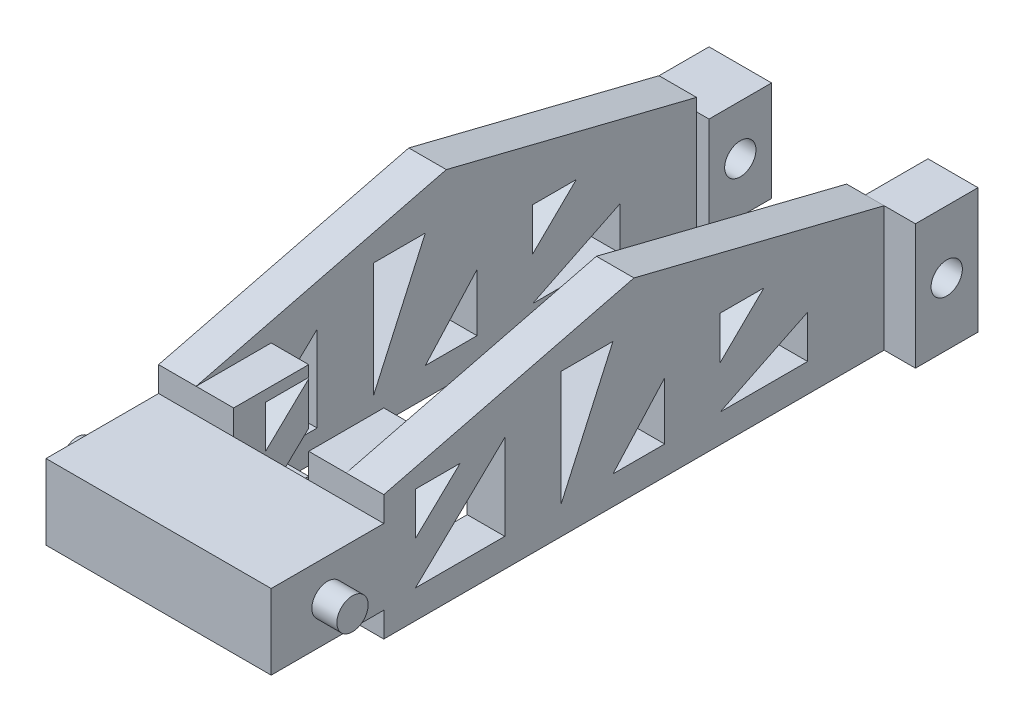
SolidWorks part; units mm, degrees
ref_plane "Front Plane" through (0, 0, 0) normal (0, 0, 1) x (1, 0, 0)
ref_plane "Top Plane" through (0, 0, 0) normal (0, 1, 0) x (1, 0, 0)
ref_plane "Right Plane" through (0, 0, 0) normal (1, 0, 0) x (0, 0, -1)
sketch "Sketch1" plane through (0, 0, 0) normal (1, 0, 0) x (0, 0, -1)
  circle A0 centre (0, 0) radius 12.5
  dimension "D1" = 25
extrude "Boss-Extrude1" add sketch "Sketch1" along normal blind 20
sketch "Sketch2" plane through (20, 0, 0) normal (1, 0, 0) x (0, 0, -1)
  line L0 (45, 30) -> (45, -30)
  line L2 (-45, 30) -> (-45, -30)
  line L3 (-45, -30) -> (45, -30)
  line L8 (-45, 30) -> (45, 30)
  line L13 (45, -30) -> (-45, 30) construction
  line L14 (45, 30) -> (-45, -30) construction
  point P0 (0, 0)
  point P2 (0, 0)
  point P8 (75, 0)
extrude "Boss-Extrude2" add sketch "Sketch2" along normal blind 90
mirror "Mirror1" about plane through (110, 0, 0) normal (-1, 0, 0) of bodies 102
sketch "Sketch6" plane through (0, 0, -45) normal (0, 0, -1) x (-1, 0, 0)
  line L1 (-140, 0) -> (-110, 0) construction
  line L3 (-20, -50) -> (-80, -50)
  line L4 (-80, 50) -> (-80, -50)
  line L5 (-20, 50) -> (-80, 50)
  line L7 (-20, 50) -> (-20, -50)
  line L8 (-200, 50) -> (-140, 50)
  line L9 (-200, 50) -> (-200, -50)
  line L10 (-200, -50) -> (-140, -50)
  line L11 (-140, 50) -> (-140, -50)
  dimension "D1" = 60
  dimension "D2" = 100
extrude "Boss-Extrude4" add sketch "Sketch6" along normal blind 400
sketch "Sketch8" plane through (0, 50, 0) normal (0, 1, 0) x (1, 0, 0)
  line L0 (20, 445) -> (80, 445) construction
  line L9 (50, 445) -> (170, 445)
  line L10 (50, 445) -> (50, 105)
  line L11 (50, 105) -> (170, 105)
  line L12 (170, 445) -> (170, 105)
extrude "Cut-Extrude4" cut sketch "Sketch8" against normal through all
sketch "Sketch9" plane through (20, 0, 0) normal (-1, 0, 0) x (0, 0, 1)
  line L2 (-445, 50) -> (-245, 100)
  line L5 (-45, 50) -> (-245, 100)
  line L8 (-445, 50) -> (-45, 50)
extrude "Boss-Extrude5" add sketch "Sketch9" against normal up to surface (30 mm away) up to face at (50, 0, -275)
sketch "Sketch10" plane through (200, 0, 0) normal (1, 0, 0) x (0, 0, -1)
  line L2 (245, 100) -> (445, 50)
  line L6 (245, 100) -> (45, 50)
  line L9 (45, 50) -> (445, 50)
extrude "Boss-Extrude6" add sketch "Sketch10" against normal up to vertex
sketch "Sketch11" plane through (200, 0, 0) normal (1, 0, 0) x (0, 0, -1)
  line L0 (70.2948, 6.9541) -> (106.0107, 41.1662)
  line L1 (70.2948, 41.1662) -> (106.0107, 41.1662)
  line L2 (70.2948, 41.1662) -> (70.2948, 6.9541)
  line L3 (70.2948, -27.258) -> (141.7267, -27.258)
  line L4 (141.7267, 41.1662) -> (141.7267, -27.258)
  line L5 (186.8415, 64.4755) -> (228.1968, 64.4755)
  line L6 (186.8415, 64.4755) -> (186.8415, -27.258)
  line L9 (228.1968, -27.258) -> (269.5521, -27.258)
  line L10 (269.5521, 18.6087) -> (269.5521, -27.258)
  line L11 (313.915, 41.1662) -> (348.879, 41.1662)
  line L12 (313.915, 41.1662) -> (313.915, 6.9541)
  line L13 (313.915, -27.258) -> (383.843, -27.258)
  line L14 (383.843, 6.9541) -> (383.843, -27.258)
  line L15 (70.2948, -27.258) -> (141.7267, 41.1662)
  line L16 (186.8415, -27.258) -> (228.1968, 64.4755)
  line L17 (228.1968, -27.258) -> (269.5521, 18.6087)
  line L18 (313.915, 6.9541) -> (348.879, 41.1662)
  line L19 (313.915, -27.258) -> (383.843, 6.9541)
  point P12 (245, 0)
extrude "Cut-Extrude6" cut sketch "Sketch11" against normal up to vertex (180 mm away) up to point (20, -50, -445)
sketch "Sketch12" plane through (0, 0, -445) normal (0, 0, -1) x (-1, 0, 0)
  line L0 (-35, 50) -> (-35, -50) construction
  line L1 (-20, 50) -> (-50, 50) construction
  line L2 (-50, -50) -> (-20, -50) construction
  line L4 (-60, -40) -> (-10, -40)
  line L5 (-60, -40) -> (-60, 40)
  line L6 (-60, 40) -> (-10, 40)
  line L7 (-10, -40) -> (-10, 40)
  line L8 (-60, -40) -> (-10, 40) construction
  line L9 (-60, 40) -> (-10, -40) construction
  point P6 (-35, 0)
  point P7 (-35, 0)
  dimension "D1" = 50
  dimension "D2" = 80
extrude "Boss-Extrude7" add sketch "Sketch12" along normal blind 50
sketch "Sketch14" plane through (0, 0, -445) normal (0, 0, -1) x (-1, 0, 0)
  line L0 (-185, 50) -> (-185, -50)
  line L1 (-170, 50) -> (-200, 50) construction
  line L2 (-200, -50) -> (-170, -50) construction
  line L3 (-185, -50) -> (-225, -50)
  line L4 (-225, -50) -> (-225, 50)
  line L5 (-225, 50) -> (-185, 50)
  dimension "D1" = 40
extrude "Boss-Extrude8" add sketch "Sketch14" along normal through all
sketch "Sketch13" plane through (60, 0, 0) normal (1, 0, 0) x (0, 0, -1)
  line L0 (470, 0) -> (445, 0) construction
  line L3 (445, 40) -> (445, -40) construction
  circle A0 centre (470, 0) radius 12.5
  dimension "D1" = 25
extrude "Cut-Extrude7" cut sketch "Sketch13" against normal blind 100 and the other way up to next
